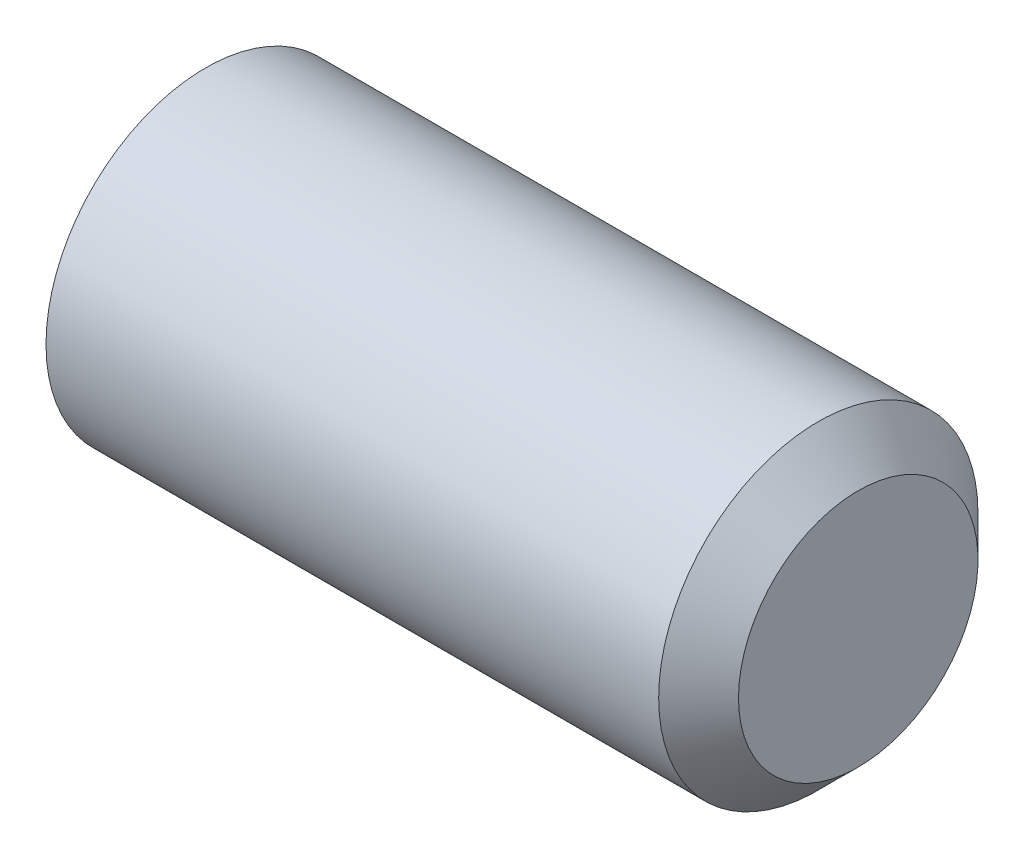
SolidWorks part; units mm, degrees
revolve "BaseBody" add sketch "BodySke" angle 360 about L5
sketch "BodySke" plane through (0, 0, 0) normal (0, 0, 1) x (1, 0, 0)
  line L0 (0, 0) -> (0, 10.352)
  line L1 (0, 10.352) -> (0.9515, 12)
  line L2 (0.9515, 12) -> (47, 12)
  line L3 (47, 12) -> (50, 9)
  line L4 (50, 0) -> (0, 0)
  line L5 (-12.7, 0) -> (88.9, 0) construction
  line L6 (50, 9) -> (50, 0)
  line L7 (50, 9) -> (50, 18.525) construction
  line L8 (0, -10.352) -> (0.9515, -12) construction
  line L9 (3, 15.875) -> (3, -3.175) construction
  line L10 (47, -12) -> (50, -9) construction
  dimension "Diameter" = 24
  dimension "Drive_ch_ang" = 60
  dimension "Minor_dia" = 20.704
  dimension "Cup_nose_ang" = 45
  dimension "Cup_dia" = 18
  dimension "Length" = 50
  dimension "Advance" = 3
cosmetic thread "ThreadCosmetic" [suppressed] parameters "Thread_minor"=20.704
ref_plane "Plane1" through (0, 0, 0) normal (0, 0, 1) x (1, 0, 0)
ref_plane "Plane2" through (0, 0, 0) normal (0, 1, 0) x (1, 0, 0)
ref_plane "Plane3" through (0, 0, 0) normal (1, 0, 0) x (0, 0, -1)
sketch "Sketch2" plane through (0, 0, 0) normal (-1, 0, 0) x (0, 0, 1)
  line L0 (3.4641, 6) -> (-3.4641, 6)
  line L1 (-3.4641, 6) -> (-6.9282, 0)
  line L2 (3.4641, 6) -> (6.9282, 0)
  line L3 (3.4641, -6) -> (6.9282, 0)
  line L4 (3.4641, -6) -> (-3.4641, -6)
  line L5 (-3.4641, -6) -> (-6.9282, 0)
  dimension "Hex_size" = 12
  dimension "D2" = 6
  dimension "D3" = 6
extrude "Hex" cut sketch "Sketch2" against normal blind 15
sketch "ThdSchSke" plane through (0, 0, 0) normal (0, 0, 1) x (1, 0, 0)
  line L0 (0.9515, -10.352) -> (-0.2025, -12)
  line L1 (0.9515, -10.352) -> (2.1054, -12)
  line L2 (2.1054, -12) -> (2.1054, -15)
  line L3 (-3.175, 0) -> (5.1513, 0) construction
  line L5 (2.1054, -15) -> (-0.2025, -15)
  line L6 (-0.2025, -15) -> (-0.2025, -12)
  line L8 (0.9515, 12) -> (0.9515, -12) construction
  dimension "Thread_minor" = 20.704
  dimension "Diameter" = 24
revolve "ThreadSchematic" [suppressed] cut sketch "ThdSchSke" angle 360 about L3
pattern_linear "ThdSchPat" [suppressed]
equation "\"D2@Sketch2\" = \"Hex_size@Sketch2\" / 2"
equation "\"D3@Sketch2\" = \"Hex_size@Sketch2\" / 2"
equation "\"Thread_minor@ThreadCosmetic\" = \"Minor_dia@BodySke\""
equation "\"Thread_minor@ThdSchSke\" = \"Thread_minor@ThreadCosmetic\""
equation "\"Diameter@ThdSchSke\" = \"Diameter@BodySke\""
equation "\"Overcut@ThdSchSke\" = \"Diameter@BodySke\" * 1.25"
equation "\"Num_threads@ThdSchPat\" = int( (\"Length@BodySke\" - ( ( ( \"Diameter@BodySke\" - \"Minor_dia@BodySke\" ) * 0.5 ) / tan( \"Drive_ch_ang@BodySke\" * 0.017453292 ) ) - ( ( ( \"Diameter@BodySke\" - \"Cup_dia@BodySke\" ) * 0.5 ) * tan( \"Cup_nose_ang@BodySke\" * 0.017453292 ) ) ) / \"Advance@BodySke\" + 0.999 )  + 1"
equation "\"Advance@ThdSchPat\" = (\"Length@BodySke\" - ( ( ( \"Diameter@BodySke\" - \"Minor_dia@BodySke\" ) * 0.5 ) / tan( \"Drive_ch_ang@BodySke\" * 0.017453292 ) ) - ( ( ( \"Diameter@BodySke\" - \"Cup_dia@BodySke\" ) * 0.5 ) * tan( \"Cup_nose_ang@BodySke\" * 0.017453292 ) ) ) /  (\"Num_threads@ThdSchPat\" - 1) 'relax it"
equation "' \"Num_threads@ThdSchPat\" = \"Num_threads@ThdSchPat\" - sgn( \"Num_threads@ThdSchPat\" - 1) '---chamfered tips only---"
